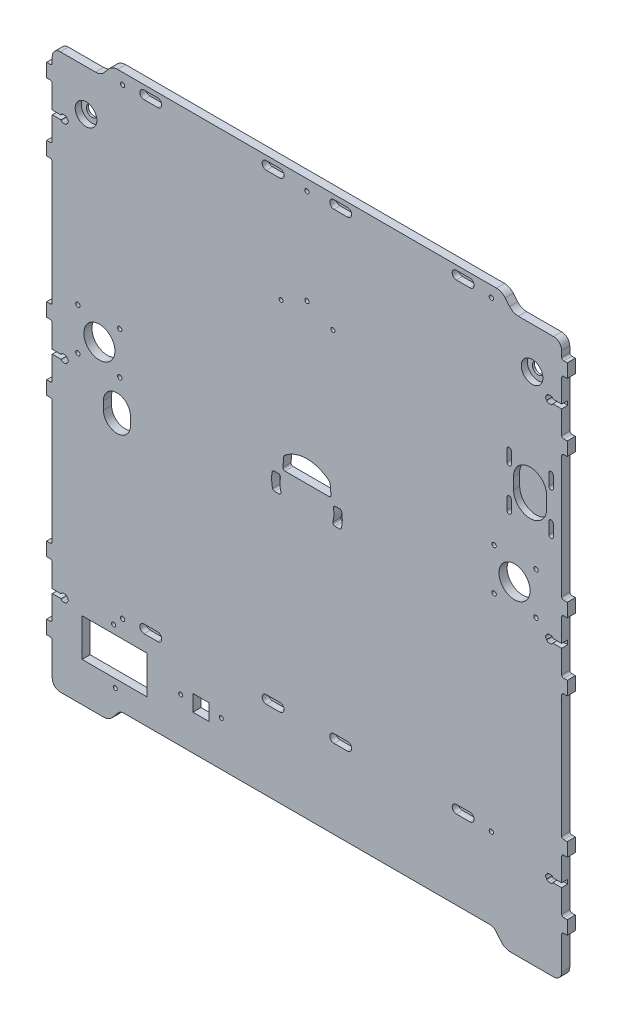
SolidWorks part; units mm, degrees
ref_plane "Alzado" through (0, 0, 0) normal (0, 0, 1) x (1, 0, 0)
ref_plane "Planta" through (0, 0, 0) normal (0, 1, 0) x (1, 0, 0)
ref_plane "Vista lateral" through (0, 0, 0) normal (1, 0, 0) x (0, 0, -1)
sketch "Croquis1" plane through (0, 0, 0) normal (0, 0, 1) x (1, 0, 0)
  line L0 (-10.6795, 26.7767) -> (-13.879, 26.7767)
  line L1 (-34.6047, 239.0104) -> (-34.6047, -170.9896) construction
  line L2 (-13.5151, 39.6941) -> (-10.3636, 39.6941)
  line L3 (-222.9547, 187.3104) -> (-34.6047, 187.3104) construction
  line L4 (-128.7797, 34.0104) -> (-128.7797, 187.3104) construction
  line L5 (-222.9547, 205.7604) -> (-222.9547, 168.8604)
  line L6 (-16.827, 45.3024) -> (-17.4546, 52.4766)
  line L7 (-50.8381, 43.6172) -> (-18.3712, 43.6172)
  line L8 (-51.7547, 52.4766) -> (-52.3823, 45.3024)
  line L9 (-227.1047, 167.3104) -> (-224.5047, 167.3104)
  line L10 (-58.5298, 26.7767) -> (-55.3303, 26.7767)
  line L11 (-55.6942, 39.6941) -> (-58.8457, 39.6941)
  line L12 (-227.1047, 157.3104) -> (-227.1047, 167.3104)
  line L13 (-224.5047, 157.3104) -> (-227.1047, 157.3104)
  line L14 (-224.5047, -89.2896) -> (-227.1047, -89.2896)
  line L15 (-227.1047, -89.2896) -> (-227.1047, -99.2896)
  line L16 (-34.6047, 34.0104) -> (-222.9547, 34.0104) construction
  line L17 (-227.1047, -99.2896) -> (-224.5047, -99.2896)
  line L18 (-18.3712, 43.6172) -> (-50.8381, 43.6172)
  line L19 (-17.4546, 52.4766) -> (-16.827, 45.3024)
  line L20 (-55.3303, 26.7767) -> (-58.5298, 26.7767)
  line L21 (-227.1047, -139.2896) -> (-224.5047, -139.2896)
  line L22 (-227.1047, -149.2896) -> (-227.1047, -139.2896)
  line L23 (-224.5047, -149.2896) -> (-227.1047, -149.2896)
  line L25 (-222.9547, -137.7396) -> (-222.9547, -100.8396)
  line L32 (147.7453, -180.9896) -> (115.7453, -180.9896)
  line L36 (100.8221, -170.9896) -> (-170.0314, -170.9896)
  line L37 (-210.4105, 34.0104) -> (-223.8121, 34.0104) construction
  line L38 (-222.9547, 15.5604) -> (-222.9547, 52.4604)
  line L42 (153.7453, 2.4611) -> (153.7453, -87.7396)
  line L43 (-227.1047, 14.0104) -> (-224.5047, 14.0104)
  line L44 (-227.1047, 4.0104) -> (-227.1047, 14.0104)
  line L45 (-224.5047, 4.0104) -> (-227.1047, 4.0104)
  line L46 (-224.5047, 64.0104) -> (-227.1047, 64.0104)
  line L47 (-227.1047, 64.0104) -> (-227.1047, 54.0104)
  line L48 (-227.1047, 54.0104) -> (-224.5047, 54.0104)
  line L49 (-185.1047, 15.6104) -> (-185.1047, 21.6104)
  line L50 (-165.1047, 21.6104) -> (-165.1047, 15.6104)
  line L51 (-204.0289, 73.6104) -> (-173.0289, 73.6104) construction
  line L52 (-200.9547, -123.9896) -> (-152.9547, -123.9896)
  line L53 (113.2425, 131.6103) -> (113.2419, 140.1103)
  line L54 (116.5488, 140.1105) -> (116.5494, 131.6105)
  line L55 (144.2425, 131.6103) -> (144.2419, 140.1103)
  line L56 (147.5488, 140.1105) -> (147.5494, 131.6105)
  line L57 (130.2626, 109.7644) -> (130.2626, 118.2644) construction
  line L58 (107.5281, 109.7644) -> (107.5281, 118.2644) construction
  line L59 (116.5488, 140.1105) -> (147.5488, 140.1105) construction
  line L60 (113.2425, 100.6103) -> (113.2419, 109.1103)
  line L61 (116.5488, 109.1105) -> (116.5494, 100.6105)
  line L62 (144.2425, 100.6103) -> (144.2419, 109.1103)
  line L63 (-34.6047, 34.0104) -> (153.7453, 34.0104) construction
  line L64 (-200.9547, -123.9896) -> (-200.9547, -151.9896)
  line L65 (-200.9547, -151.9896) -> (-152.9547, -151.9896)
  line L66 (-152.9547, -123.9896) -> (-152.9547, -151.9896)
  line L67 (-118.9547, -132.8214) -> (-106.9547, -132.8214)
  line L68 (-118.9547, -132.8214) -> (-118.9547, -144.8214)
  line L69 (109.234, -177.9533) -> (105.0418, -172.9573)
  line L73 (-222.9547, 155.7604) -> (-222.9547, 65.5604)
  line L74 (-222.9547, 2.4611) -> (-222.9547, -87.7396)
  line L75 (-222.9547, -150.8396) -> (-222.9547, -174.9896)
  line L77 (153.7453, -150.8396) -> (153.7453, -174.9896)
  line L81 (157.8953, -99.2896) -> (155.2953, -99.2896)
  line L82 (157.8953, -89.2896) -> (157.8953, -99.2896)
  line L83 (155.2953, -89.2896) -> (157.8953, -89.2896)
  line L84 (155.2953, -149.2896) -> (157.8953, -149.2896)
  line L85 (157.8953, -149.2896) -> (157.8953, -139.2896)
  line L86 (157.8953, -139.2896) -> (155.2953, -139.2896)
  line L87 (153.7453, -137.7396) -> (153.7453, -100.8396)
  line L91 (155.2953, 4.0104) -> (157.8953, 4.0104)
  line L92 (157.8953, 4.0104) -> (157.8953, 14.0104)
  line L93 (157.8953, 14.0104) -> (155.2953, 14.0104)
  line L94 (-118.9547, -144.8214) -> (-106.9547, -144.8214)
  line L95 (-106.9547, -132.8214) -> (-106.9547, -144.8214)
  line L96 (-118.9547, -132.8214) -> (-106.9547, -144.8214) construction
  line L97 (-118.9547, -144.8214) -> (-106.9547, -132.8214) construction
  line L98 (-204.0289, 73.6104) -> (-204.0289, 42.6104) construction
  line L99 (134.8196, 73.6104) -> (134.8196, 42.6104) construction
  line L100 (134.8196, 73.6104) -> (103.8196, 73.6104) construction
  line L101 (118.8953, 57.6104) -> (118.8953, 118.2644) construction
  line L102 (147.5488, 109.1105) -> (147.5494, 100.6105)
  line L103 (153.7453, 15.5604) -> (153.7453, 52.4604)
  line L104 (157.8953, 54.0104) -> (155.2953, 54.0104)
  line L105 (157.8953, 64.0104) -> (157.8953, 54.0104)
  line L106 (155.2953, 64.0104) -> (157.8953, 64.0104)
  line L107 (153.7453, 155.7604) -> (153.7453, 65.5604)
  line L108 (155.2953, 157.3104) -> (157.8953, 157.3104)
  line L109 (157.8953, 157.3104) -> (157.8953, 167.3104)
  line L110 (157.8953, 167.3104) -> (155.2953, 167.3104)
  line L115 (153.7453, 205.7604) -> (153.7453, 168.8604)
  line L116 (157.8953, 207.3104) -> (155.2953, 207.3104)
  line L117 (157.8953, 217.3104) -> (157.8953, 207.3104)
  line L118 (155.2953, 217.3104) -> (157.8953, 217.3104)
  line L119 (153.7453, 223.1104) -> (153.7453, 218.8604)
  line L120 (121.7453, 229.1104) -> (147.7453, 229.1104)
  line L121 (112.0224, 235.9741) -> (115.234, 232.1467)
  line L131 (105.511, 239.0104) -> (-174.7203, 239.0104)
  line L132 (-181.2317, 235.9741) -> (-184.4433, 232.1467)
  line L133 (-190.9547, 229.1104) -> (-216.9547, 229.1104)
  line L134 (-222.9547, 223.1104) -> (-222.9547, 218.8604)
  line L135 (-224.5047, 217.3104) -> (-227.1047, 217.3104)
  line L136 (-227.1047, 217.3104) -> (-227.1047, 207.3104)
  line L137 (-227.1047, 207.3104) -> (-224.5047, 207.3104)
  line L142 (-216.9547, -180.9896) -> (-184.9547, -180.9896)
  line L143 (-178.4433, -177.9533) -> (-174.2511, -172.9573)
  line L145 (-222.9547, 110.6604) -> (-34.6047, 110.6604) construction
  arc A0 (-8.8356, 38.4045) -> (-9.1714, 27.9685) centre (-34.6047, 34.0104) cw
  arc A1 (-9.1714, 27.9685) -> (-10.6795, 26.7767) centre (-10.6795, 28.3268) cw
  arc A2 (-222.9547, 168.8604) -> (-224.5047, 167.3104) centre (-224.5047, 168.8604) cw
  arc A3 (-224.5047, 157.3104) -> (-222.9547, 155.7604) centre (-224.5047, 155.7604) cw
  arc A4 (-13.879, 26.7767) -> (-15.3739, 28.7367) centre (-13.879, 28.3268) cw
  arc A5 (-15.0363, 37.8458) -> (-15.3739, 28.7367) centre (-34.6047, 34.0104) cw
  arc A6 (-15.0363, 37.8458) -> (-13.5151, 39.6941) centre (-13.5151, 38.144) cw
  arc A7 (-224.5047, -89.2896) -> (-222.9547, -87.7396) centre (-224.5047, -87.7396) ccw
  arc A8 (-222.9547, -100.8396) -> (-224.5047, -99.2896) centre (-224.5047, -100.8396) ccw
  arc A9 (-222.9547, -137.7396) -> (-224.5047, -139.2896) centre (-224.5047, -137.7396) cw
  arc A10 (-18.3712, 43.6172) -> (-16.827, 45.3024) centre (-18.3712, 45.1673) ccw
  arc A11 (-52.3823, 45.3024) -> (-50.8381, 43.6172) centre (-50.8381, 45.1673) ccw
  arc A12 (-51.2153, 53.5218) -> (-51.7547, 52.4766) centre (-50.2105, 52.3415) ccw
  arc A13 (-17.994, 53.5218) -> (-51.2153, 53.5218) centre (-34.6047, 34.0104) ccw
  arc A14 (-17.4546, 52.4766) -> (-17.994, 53.5218) centre (-18.9988, 52.3415) ccw
  arc A15 (-224.5047, -149.2896) -> (-222.9547, -150.8396) centre (-224.5047, -150.8396) cw
  arc A16 (-10.3636, 39.6941) -> (-8.8356, 38.4045) centre (-10.3636, 38.144) cw
  arc A18 (-222.9547, -174.9896) -> (-216.9547, -180.9896) centre (-216.9547, -174.9896) ccw
  arc A22 (-55.3303, 26.7767) -> (-53.8354, 28.7367) centre (-55.3303, 28.3268) ccw
  arc A23 (-60.0379, 27.9685) -> (-58.5298, 26.7767) centre (-58.5298, 28.3268) ccw
  arc A24 (-60.3738, 38.4045) -> (-60.0379, 27.9685) centre (-34.6047, 34.0104) ccw
  arc A25 (-58.8457, 39.6941) -> (-60.3738, 38.4045) centre (-58.8457, 38.144) ccw
  arc A26 (-54.173, 37.8458) -> (-55.6942, 39.6941) centre (-55.6942, 38.144) ccw
  arc A27 (-54.173, 37.8458) -> (-53.8354, 28.7367) centre (-34.6047, 34.0104) ccw
  arc A28 (-222.9547, 15.5604) -> (-224.5047, 14.0104) centre (-224.5047, 15.5604) cw
  arc A29 (-224.5047, 4.0104) -> (-222.9547, 2.4604) centre (-224.5047, 2.4604) cw
  arc A30 (-224.5047, 64.0104) -> (-222.9547, 65.5604) centre (-224.5047, 65.5604) ccw
  arc A31 (-222.9547, 52.4604) -> (-224.5047, 54.0104) centre (-224.5047, 52.4604) ccw
  arc A40 (100.8221, -170.9896) -> (105.0418, -172.9573) centre (100.8221, -176.498) cw
  arc A41 (115.7453, -180.9896) -> (109.234, -177.9533) centre (115.7453, -172.4896) cw
  arc A42 (153.7453, -174.9896) -> (147.7453, -180.9896) centre (147.7453, -174.9896) cw
  arc A45 (153.7453, -100.8396) -> (155.2953, -99.2896) centre (155.2953, -100.8396) cw
  arc A46 (-17.994, 53.5218) -> (-51.2153, 53.5218) centre (-34.6047, 34.0104) ccw
  arc A47 (-17.4546, 52.4766) -> (-17.994, 53.5218) centre (-18.9988, 52.3415) ccw
  arc A48 (-18.3712, 43.6172) -> (-16.827, 45.3024) centre (-18.3712, 45.1673) ccw
  arc A49 (-52.3823, 45.3024) -> (-50.8381, 43.6172) centre (-50.8381, 45.1673) ccw
  arc A50 (-51.2153, 53.5218) -> (-51.7547, 52.4766) centre (-50.2105, 52.3415) ccw
  arc A51 (-58.8457, 39.6941) -> (-60.3738, 38.4045) centre (-58.8457, 38.144) ccw
  arc A52 (-60.3738, 38.4045) -> (-60.0379, 27.9685) centre (-34.6047, 34.0104) ccw
  arc A53 (-60.0379, 27.9685) -> (-58.5298, 26.7767) centre (-58.5298, 28.3268) ccw
  arc A54 (-55.3303, 26.7767) -> (-53.8354, 28.7367) centre (-55.3303, 28.3268) ccw
  arc A55 (-54.173, 37.8458) -> (-53.8354, 28.7367) centre (-34.6047, 34.0104) ccw
  arc A56 (-54.173, 37.8458) -> (-55.6942, 39.6941) centre (-55.6942, 38.144) ccw
  arc A62 (155.2953, -89.2896) -> (153.7453, -87.7396) centre (155.2953, -87.7396) cw
  arc A63 (155.2953, -149.2896) -> (153.7453, -150.8396) centre (155.2953, -150.8396) ccw
  arc A64 (153.7453, -137.7396) -> (155.2953, -139.2896) centre (155.2953, -137.7396) ccw
  arc A68 (155.2953, 4.0104) -> (153.7453, 2.4604) centre (155.2953, 2.4604) ccw
  arc A69 (153.7453, 15.5604) -> (155.2953, 14.0104) centre (155.2953, 15.5604) ccw
  circle A70 centre (101.7453, 231.0104) radius 1.6
  circle A71 centre (-34.6047, 231.0104) radius 1.6
  circle A73 centre (101.7453, -110.9896) radius 1.6
  circle A74 centre (-177.5547, -117.9896) radius 1.5
  arc A75 (153.7453, 52.4604) -> (155.2953, 54.0104) centre (155.2953, 52.4604) cw
  arc A76 (155.2953, 64.0104) -> (153.7453, 65.5604) centre (155.2953, 65.5604) cw
  arc A77 (155.2953, 157.3104) -> (153.7453, 155.7604) centre (155.2953, 155.7604) ccw
  arc A78 (153.7453, 168.8604) -> (155.2953, 167.3104) centre (155.2953, 168.8604) ccw
  arc A83 (153.7453, 205.7604) -> (155.2953, 207.3104) centre (155.2953, 205.7604) cw
  arc A84 (155.2953, 217.3104) -> (153.7453, 218.8604) centre (155.2953, 218.8604) cw
  arc A85 (147.7453, 229.1104) -> (153.7453, 223.1104) centre (147.7453, 223.1104) cw
  arc A86 (121.7453, 229.1104) -> (115.234, 232.1467) centre (121.7453, 237.6104) cw
  arc A87 (105.511, 239.0104) -> (112.0224, 235.9741) centre (105.511, 230.5104) cw
  circle A88 centre (-176.3547, -157.9896) radius 1.5
  arc A89 (-174.7203, 239.0104) -> (-181.2317, 235.9741) centre (-174.7203, 230.5104) ccw
  arc A90 (-190.9547, 229.1104) -> (-184.4433, 232.1467) centre (-190.9547, 237.6104) ccw
  arc A91 (-216.9547, 229.1104) -> (-222.9547, 223.1104) centre (-216.9547, 223.1104) ccw
  arc A92 (-224.5047, 217.3104) -> (-222.9547, 218.8604) centre (-224.5047, 218.8604) ccw
  arc A93 (-222.9547, 205.7604) -> (-224.5047, 207.3104) centre (-224.5047, 205.7604) ccw
  arc A97 (-184.9547, -180.9896) -> (-178.4433, -177.9533) centre (-184.9547, -172.4896) ccw
  arc A98 (-170.0314, -170.9896) -> (-174.2511, -172.9573) centre (-170.0314, -176.498) ccw
  circle A99 centre (-188.1047, 57.6104) radius 11.5
  circle A100 centre (-204.0289, 73.6104) radius 1.6
  circle A101 centre (-173.0289, 73.6104) radius 1.6
  circle A102 centre (-204.0289, 42.6104) radius 1.6
  circle A103 centre (-173.0289, 42.6104) radius 1.6
  arc A104 (-165.1047, 21.6104) -> (-185.1047, 21.6104) centre (-175.1047, 21.6104) ccw
  arc A105 (-185.1047, 15.6104) -> (-165.1047, 15.6104) centre (-175.1047, 15.6104) ccw
  circle A106 centre (-127.9547, -137.9896) radius 1.5
  circle A107 centre (-197.9547, 198.6104) radius 4.25
  circle A108 centre (-170.9547, 231.0104) radius 1.6
  circle A109 centre (-97.9547, -137.9896) radius 1.5
  circle A110 centre (103.8196, 42.6104) radius 1.6
  circle A111 centre (134.8196, 42.6104) radius 1.6
  circle A112 centre (103.8196, 73.6104) radius 1.6
  circle A113 centre (131.8953, 198.6104) radius 4.25
  arc A114 (116.5488, 140.1105) -> (113.2419, 140.1103) centre (114.8953, 140.1104) ccw
  arc A115 (113.2425, 131.6103) -> (116.5494, 131.6105) centre (114.8959, 131.6104) ccw
  arc A116 (147.5488, 140.1105) -> (144.2419, 140.1103) centre (145.8953, 140.1104) ccw
  arc A117 (144.2425, 131.6103) -> (147.5494, 131.6105) centre (145.8959, 131.6104) ccw
  arc A118 (130.2626, 118.2644) -> (107.5281, 118.2644) centre (118.8953, 118.2644) ccw construction
  arc A119 (107.5281, 109.7644) -> (130.2626, 109.7644) centre (118.8953, 109.7644) ccw construction
  arc A120 (116.5488, 109.1105) -> (113.2419, 109.1103) centre (114.8953, 109.1104) ccw
  arc A121 (113.2425, 100.6103) -> (116.5494, 100.6105) centre (114.8959, 100.6104) ccw
  arc A122 (147.5488, 109.1105) -> (144.2419, 109.1103) centre (145.8953, 109.1104) ccw
  arc A123 (144.2425, 100.6103) -> (147.5494, 100.6105) centre (145.8959, 100.6104) ccw
  circle A124 centre (134.8196, 73.6104) radius 1.6
  circle A125 centre (118.8953, 57.6104) radius 11.5
  circle A133 centre (-170.9547, -110.9896) radius 1.6
  point P250 (-112.9547, -138.8214)
  dimension "D1" = 8.5
  dimension "D3" = 8.5
  dimension "D4" = 6
  dimension "D8" = 1.55
  dimension "D11" = 1.55
  dimension "D12" = 25
  dimension "D14" = 8.5
  dimension "D15" = 25.6244
  dimension "D21" = 6
  dimension "D23" = 40
  dimension "D26" = 8
  dimension "D27" = 32
  dimension "D29" = 3.2
  dimension "D30" = 8.5
  dimension "D7" = 3.2
  dimension "D31" = 48
  dimension "D38" = 6
  dimension "D39" = 6
  dimension "D40" = 25
  dimension "D45" = 9
  dimension "D47" = 3.2
  dimension "D54" = 23
  dimension "D57" = 10
  dimension "D58" = 10
  dimension "D63" = 89
  dimension "D64" = 8.5
  dimension "D65" = 1.6534
  dimension "D66" = 1.6534
  dimension "D20" = 1.5501
  dimension "D67" = 1.5501
  dimension "D71" = 1.5501
  dimension "D72" = 1.5501
  dimension "D75" = 1.5501
  dimension "D77" = 1.5501
  dimension "D78" = 26.1411
  dimension "D79" = 1.5501
  dimension "D81" = 1.5501
  dimension "D82" = 19.9407
  dimension "D87" = 1.55
  dimension "D88" = 1.55
  dimension "D2" = 50
  dimension "D5" = 8
  dimension "D6" = 52
  dimension "D9" = 10
  dimension "D10" = 2.6
  dimension "D13" = 40.4
  dimension "D16" = 21.85
  dimension "D17" = 11.8
  dimension "D18" = 32
  dimension "D19" = 15.9
  dimension "D22" = 7.1742
  dimension "D24" = 40.4
  dimension "D25" = 38.85
  dimension "D28" = 52
  dimension "D32" = 10
  dimension "D62" = 7.1682
  dimension "D89" = 22.5
  dimension "D33" = 6.5218
  dimension "D34" = 50
  dimension "D35" = 28
  dimension "D36" = 13
  dimension "D37" = 22
  dimension "D41" = 14
  dimension "D42" = 12
  dimension "D43" = 12
  dimension "D44" = 9
  dimension "D46" = 14
  dimension "D48" = 2
  dimension "D49" = 31
  dimension "D51" = 31
  dimension "D52" = 16
  dimension "D53" = 36
  dimension "D55" = 141
  dimension "D56" = 39
  dimension "D59" = 6
  dimension "D60" = 6
  dimension "D61" = 52
  dimension "D68" = 2
  dimension "D69" = 31
  dimension "D73" = 7.1742
  dimension "D74" = 32.467
  dimension "D76" = 3.1515
  dimension "D80" = 3.1995
  dimension "D83" = 24.2411
  dimension "D84" = 23.9251
  dimension "D85" = 10
  dimension "D86" = 2.6
  dimension "D50" = 2
  dimension "D70" = 2
extrude "Saliente-Extruir1" add sketch "Croquis1" along normal blind 6
sketch "Croquis10" plane through (0, 0, 6) normal (0, 0, 1) x (1, 0, 0)
  line L0 (142.672, 116.1611) -> (142.672, 124.6104)
  line L1 (118.2177, 116.019) -> (118.1195, 124.4678)
  line L2 (114.8953, 140.1104) -> (145.8953, 109.1104) construction
  line L3 (-216.4544, 188.8604) -> (-222.9547, 188.8604)
  line L4 (-209.8753, 187.3104) -> (-223.8121, 187.3104) construction
  line L5 (-214.9445, 190.0604) -> (-213.3945, 190.0604)
  line L6 (-211.8813, 188.8465) -> (-211.8813, 188.6773)
  line L7 (-222.9547, 34.0104) -> (153.7453, 34.0104) construction
  line L8 (-211.8813, 185.9436) -> (-211.8813, 185.7743)
  line L9 (-214.9445, 184.5604) -> (-213.3945, 184.5604)
  line L10 (-222.9547, 188.8604) -> (-222.9547, 185.7604)
  line L11 (-34.6047, 239.0104) -> (-34.6047, -170.9896) construction
  line L12 (105.511, 239.0104) -> (-174.7203, 239.0104) construction
  line L13 (100.8221, -170.9896) -> (-170.0314, -170.9896) construction
  line L14 (-222.9547, 15.5604) -> (-222.9547, 52.4604) construction
  line L15 (-216.4544, 185.7604) -> (-222.9547, 185.7604)
  line L16 (-222.9547, 110.6604) -> (-34.6047, 110.6604) construction
  line L17 (-222.9547, 155.7604) -> (-222.9547, 65.5604) construction
  line L18 (-209.8753, 34.0104) -> (-223.8121, 34.0104) construction
  line L19 (-216.4544, 35.5604) -> (-222.9547, 35.5604)
  line L20 (-222.9547, 32.4604) -> (-222.9547, 35.5604)
  line L21 (-214.9445, 36.7604) -> (-213.3945, 36.7604)
  line L22 (-211.8813, 35.3773) -> (-211.8813, 35.5465)
  line L23 (-211.8813, 32.4743) -> (-211.8813, 32.6436)
  line L24 (-214.9445, 31.2604) -> (-213.3945, 31.2604)
  line L25 (-216.4544, 32.4604) -> (-222.9547, 32.4604)
  line L26 (-209.8753, -119.2896) -> (-223.8121, -119.2896) construction
  line L27 (-216.4544, -117.7396) -> (-222.9547, -117.7396)
  line L28 (-222.9547, -120.8396) -> (-222.9547, -117.7396)
  line L29 (-214.9445, -116.5396) -> (-213.3945, -116.5396)
  line L30 (-211.8813, -117.9227) -> (-211.8813, -117.7535)
  line L31 (-211.8813, -120.8257) -> (-211.8813, -120.6564)
  line L32 (-214.9445, -122.0396) -> (-213.3945, -122.0396)
  line L33 (-216.4544, -120.8396) -> (-222.9547, -120.8396)
  line L34 (140.666, -119.2896) -> (154.6028, -119.2896) construction
  line L35 (147.2451, -120.8396) -> (153.7453, -120.8396)
  line L36 (145.7352, -122.0396) -> (144.1852, -122.0396)
  line L37 (142.672, -120.8257) -> (142.672, -120.6564)
  line L38 (142.672, -117.9227) -> (142.672, -117.7535)
  line L39 (145.7352, -116.5396) -> (144.1852, -116.5396)
  line L40 (153.7453, -120.8396) -> (153.7453, -117.7396)
  line L41 (147.2451, -117.7396) -> (153.7453, -117.7396)
  line L42 (140.666, 34.0104) -> (154.6028, 34.0104) construction
  line L43 (147.2451, 32.4604) -> (153.7453, 32.4604)
  line L44 (145.7352, 31.2604) -> (144.1852, 31.2604)
  line L45 (142.672, 32.4743) -> (142.672, 32.6436)
  line L46 (142.672, 35.3773) -> (142.672, 35.5465)
  line L47 (145.7352, 36.7604) -> (144.1852, 36.7604)
  line L48 (153.7453, 32.4604) -> (153.7453, 35.5604)
  line L49 (147.2451, 35.5604) -> (153.7453, 35.5604)
  line L50 (140.666, 187.3104) -> (154.6028, 187.3104) construction
  line L51 (147.2451, 185.7604) -> (153.7453, 185.7604)
  line L52 (153.7453, 188.8604) -> (153.7453, 185.7604)
  line L53 (145.7352, 184.5604) -> (144.1852, 184.5604)
  line L54 (142.672, 185.9436) -> (142.672, 185.7743)
  line L55 (142.672, 188.8465) -> (142.672, 188.6773)
  line L56 (145.7352, 190.0604) -> (144.1852, 190.0604)
  line L57 (147.2451, 188.8604) -> (153.7453, 188.8604)
  line L58 (-64.6047, 235.6104) -> (-54.6047, 235.6104)
  line L59 (-64.6047, 229.4104) -> (-54.6047, 229.4104)
  line L60 (153.7453, 15.5604) -> (153.7453, 52.4604) construction
  line L61 (-155.1047, 235.6104) -> (-145.1047, 235.6104)
  line L62 (-155.1047, 229.4104) -> (-145.1047, 229.4104)
  line L63 (-54.6047, 229.4104) -> (-145.1047, 229.4104) construction
  line L64 (-4.6047, 229.4104) -> (-14.6047, 229.4104)
  line L65 (-4.6047, 235.6104) -> (-14.6047, 235.6104)
  line L66 (85.8953, 235.6104) -> (75.8953, 235.6104)
  line L67 (85.8953, 229.4104) -> (75.8953, 229.4104)
  line L68 (-64.6047, -112.5896) -> (-54.6047, -112.5896)
  line L69 (-64.6047, -106.3896) -> (-54.6047, -106.3896)
  line L70 (-155.1047, -106.3896) -> (-145.1047, -106.3896)
  line L71 (-155.1047, -112.5896) -> (-145.1047, -112.5896)
  line L72 (-4.6047, -112.5896) -> (-14.6047, -112.5896)
  line L73 (-4.6047, -106.3896) -> (-14.6047, -106.3896)
  line L74 (85.8953, -106.3896) -> (75.8953, -106.3896)
  line L75 (85.8953, -112.5896) -> (75.8953, -112.5896)
  line L76 (-54.6047, 229.4104) -> (-54.6047, -112.5896) construction
  line L77 (145.8953, 140.1104) -> (114.8953, 109.1104) construction
  line L78 (-190.9547, 229.1104) -> (-216.9547, 229.1104) construction
  line L79 (-227.1047, 64.0104) -> (-227.1047, 54.0104) construction
  line L80 (-227.1047, 59.0104) -> (157.8953, 59.0104) construction
  line L81 (157.8953, 64.0104) -> (157.8953, 54.0104) construction
  line L82 (-222.9547, 205.7604) -> (-222.9547, 168.8604) construction
  arc A0 (142.672, 124.6104) -> (118.1195, 124.4678) centre (130.3953, 124.6104) ccw
  arc A1 (118.2177, 116.019) -> (142.672, 116.1611) centre (130.4444, 116.1611) ccw
  arc A2 (-214.9445, 36.7604) -> (-216.4544, 35.5604) centre (-214.9445, 35.2104) ccw
  circle A3 centre (131.8953, 198.6104) radius 4.25
  arc A4 (-211.8813, 32.4743) -> (-213.3945, 31.2604) centre (-213.3945, 32.8104) cw
  arc A5 (-214.9445, 31.2604) -> (-216.4544, 32.4604) centre (-214.9445, 32.8104) cw
  arc A6 (-211.8813, 35.5465) -> (-213.3945, 36.7604) centre (-213.3945, 35.2104) ccw
  arc A7 (-211.8813, 35.3773) -> (-211.8813, 32.6436) centre (-212.6118, 34.0104) cw
  arc A8 (-211.8813, 185.9436) -> (-211.8813, 188.6773) centre (-212.6118, 187.3104) ccw
  arc A9 (-214.9445, -116.5396) -> (-216.4544, -117.7396) centre (-214.9445, -118.0896) ccw
  arc A10 (-211.8813, -120.8257) -> (-213.3945, -122.0396) centre (-213.3945, -120.4896) cw
  arc A11 (-214.9445, -122.0396) -> (-216.4544, -120.8396) centre (-214.9445, -120.4896) cw
  arc A12 (-211.8813, -117.7535) -> (-213.3945, -116.5396) centre (-213.3945, -118.0896) ccw
  arc A13 (-211.8813, -117.9227) -> (-211.8813, -120.6564) centre (-212.6118, -119.2896) cw
  arc A14 (142.672, -117.9227) -> (142.672, -120.6564) centre (143.4025, -119.2896) ccw
  arc A15 (142.672, -117.7535) -> (144.1852, -116.5396) centre (144.1852, -118.0896) cw
  arc A16 (145.7352, -122.0396) -> (147.2451, -120.8396) centre (145.7352, -120.4896) ccw
  arc A17 (142.672, -120.8257) -> (144.1852, -122.0396) centre (144.1852, -120.4896) ccw
  arc A18 (145.7352, -116.5396) -> (147.2451, -117.7396) centre (145.7352, -118.0896) cw
  arc A19 (142.672, 35.3773) -> (142.672, 32.6436) centre (143.4025, 34.0104) ccw
  arc A20 (142.672, 35.5465) -> (144.1852, 36.7604) centre (144.1852, 35.2104) cw
  arc A21 (145.7352, 31.2604) -> (147.2451, 32.4604) centre (145.7352, 32.8104) ccw
  arc A22 (142.672, 32.4743) -> (144.1852, 31.2604) centre (144.1852, 32.8104) ccw
  arc A23 (145.7352, 36.7604) -> (147.2451, 35.5604) centre (145.7352, 35.2104) cw
  arc A24 (145.7352, 184.5604) -> (147.2451, 185.7604) centre (145.7352, 186.1104) ccw
  arc A25 (142.672, 188.8465) -> (144.1852, 190.0604) centre (144.1852, 188.5104) cw
  arc A26 (145.7352, 190.0604) -> (147.2451, 188.8604) centre (145.7352, 188.5104) cw
  arc A27 (142.672, 185.7743) -> (144.1852, 184.5604) centre (144.1852, 186.1104) ccw
  arc A28 (142.672, 185.9436) -> (142.672, 188.6773) centre (143.4025, 187.3104) cw
  arc A29 (-54.6047, 229.4104) -> (-54.6047, 235.6104) centre (-54.6047, 232.5104) ccw
  arc A30 (-64.6047, 235.6104) -> (-64.6047, 229.4104) centre (-64.6047, 232.5104) ccw
  arc A31 (-145.1047, 229.4104) -> (-145.1047, 235.6104) centre (-145.1047, 232.5104) ccw
  arc A32 (-155.1047, 235.6104) -> (-155.1047, 229.4104) centre (-155.1047, 232.5104) ccw
  arc A33 (-14.6047, 229.4104) -> (-14.6047, 235.6104) centre (-14.6047, 232.5104) cw
  arc A34 (-4.6047, 235.6104) -> (-4.6047, 229.4104) centre (-4.6047, 232.5104) cw
  arc A35 (75.8953, 229.4104) -> (75.8953, 235.6104) centre (75.8953, 232.5104) cw
  arc A36 (85.8953, 235.6104) -> (85.8953, 229.4104) centre (85.8953, 232.5104) cw
  arc A37 (-54.6047, -112.5896) -> (-54.6047, -106.3896) centre (-54.6047, -109.4896) ccw
  arc A38 (-64.6047, -106.3896) -> (-64.6047, -112.5896) centre (-64.6047, -109.4896) ccw
  arc A39 (-145.1047, -112.5896) -> (-145.1047, -106.3896) centre (-145.1047, -109.4896) ccw
  arc A40 (-155.1047, -106.3896) -> (-155.1047, -112.5896) centre (-155.1047, -109.4896) ccw
  arc A41 (-14.6047, -112.5896) -> (-14.6047, -106.3896) centre (-14.6047, -109.4896) cw
  arc A42 (-4.6047, -106.3896) -> (-4.6047, -112.5896) centre (-4.6047, -109.4896) cw
  arc A43 (75.8953, -112.5896) -> (75.8953, -106.3896) centre (75.8953, -109.4896) cw
  arc A44 (85.8953, -106.3896) -> (85.8953, -112.5896) centre (85.8953, -109.4896) cw
  circle A45 centre (-197.9547, 198.6104) radius 8
  circle A46 centre (131.8953, 198.6104) radius 8
  circle A47 centre (131.8953, 198.6104) radius 4.25 construction
  arc A63 (-211.8813, 185.7743) -> (-213.3945, 184.5604) centre (-213.3945, 186.1104) cw
  arc A65 (-214.9445, 190.0604) -> (-216.4544, 188.8604) centre (-214.9445, 188.5104) ccw
  arc A66 (-211.8813, 188.8465) -> (-213.3945, 190.0604) centre (-213.3945, 188.5104) ccw
  arc A67 (-214.9445, 184.5604) -> (-216.4544, 185.7604) centre (-214.9445, 186.1104) cw
  point P203 (130.3953, 124.6104)
  dimension "D4" = 6.2
  dimension "D5" = 10
  dimension "D12" = 6.5002
  dimension "D2" = 16
  dimension "D3" = 16
  dimension "D13" = 1.55
  dimension "D15" = 1.55
  dimension "D17" = 1.5498
  dimension "D6" = 20
  dimension "D7" = 6.5
  dimension "D10" = 15.85
  dimension "D14" = 1.55
  dimension "D16" = 0.1692
  dimension "D18" = 41.8
  dimension "D19" = 1.55
  dimension "D20" = 1.2
  dimension "D23" = 2.7365
  dimension "D24" = 1.3669
  dimension "D8" = 2
  dimension "D11" = 2
extrude "Cortar-Extruir4" cut sketch "Croquis10" against normal blind 4.5
chamfer "Chaflán1" distance 1.5 angle 45 17 edges at (-96.4547, -137.9896, 0) (-126.4547, -137.9896, 0) (-174.8547, -157.9896, 0) (-176.0547, -117.9896, 0) (-169.3547, -110.9896, 0) (103.3453, -110.9896, 0) (136.4196, 42.6104, 0) (105.4196, 42.6104, 0) (105.4196, 73.6104, 0) (136.4196, 73.6104, 0) (-202.4289, 42.6104, 0) (-171.4289, 42.6104, 0) (-171.4289, 73.6104, 0) (-202.4289, 73.6104, 0) (-169.3547, 231.0104, 0) (-33.0047, 231.0104, 0) (103.3453, 231.0104, 0)
sketch "Croquis11" plane through (0, 0, 6) normal (0, 0, 1) x (1, 0, 0)
  line L0 (114.8952, 141.7638) -> (-222.9547, 141.7638) construction
  line L1 (-222.9547, 155.7604) -> (-222.9547, 65.5604) construction
  line L2 (-34.6047, 231.0104) -> (-34.6047, -170.9896) construction
  line L3 (100.8221, -170.9896) -> (-170.0314, -170.9896) construction
  line L4 (-222.9547, 151.7638) -> (153.7453, 151.7638) construction
  line L5 (153.7453, 155.7604) -> (153.7453, 65.5604) construction
  line L6 (-38.9828, 160.7638) -> (-30.5384, 160.7638) construction
  circle A0 centre (-34.6047, 231.0104) radius 1.6 construction
  circle A1 centre (-34.6047, 231.0104) radius 1.6
  arc A2 (116.5488, 140.1105) -> (113.2419, 140.1103) centre (114.8953, 140.1104) ccw construction
  arc A3 (116.5488, 140.1105) -> (113.2419, 140.1103) centre (114.8953, 140.1104) ccw
  circle A4 centre (-53.7847, 151.7638) radius 1.5
  circle A5 centre (-15.4247, 151.7638) radius 1.5
  circle A6 centre (-34.6047, 160.7638) radius 1.6
  dimension "D2" = 19.18
  dimension "D3" = 19.18
  dimension "D1" = 10
  dimension "D4" = 38.36
  dimension "D5" = 9
extrude "Cortar-Extruir5" cut sketch "Croquis11" against normal blind 6 contours A4 | A5 | A6
equation "\"Ancho_panel\"= 385'Ancho del panel"
equation "\"Alto_panel\"= 420'Alto del panel izquierdo"
equation "\"Altura_base_taladros\"= 70'Alto taladros de la base eje Z"
equation "\"Altura_superior_taladros\"= 8mm'Distancia taladros a top"
equation "\"Distancia_vert_entre_horizontales_ensambles\"= \"Alto_panel\" - \"Altura_base_taladros\" - \"Altura_superior_taladros\"'Distancia vertical entre horizontales de ensambles"
equation "\"Latrales_separacion_barras_a_escalon_bajo\"= 12.5'Separación entre las barras y el escalón inferior de la parte superior"
equation "\"Espacio_tensor_correa_motor\"= 8.5mm'Espacio para mover el motor en vertical y tensar la correa"
